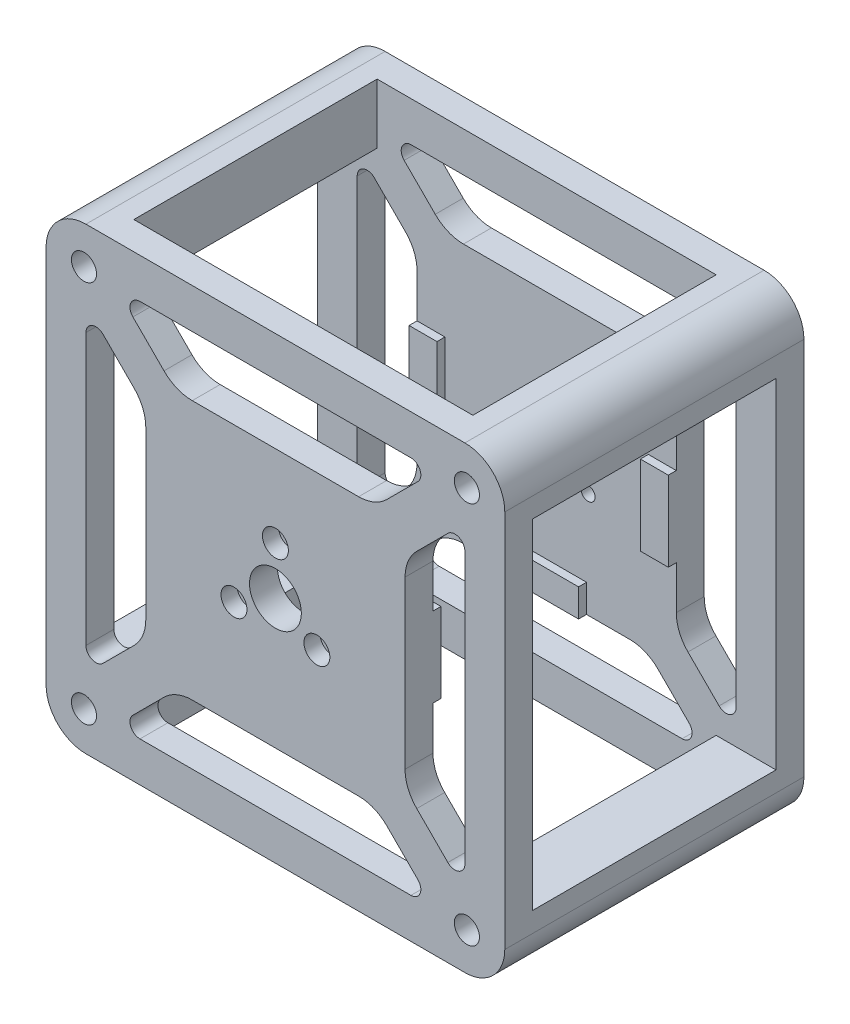
SolidWorks part; units mm, degrees
ref_plane "Front Plane" through (0, 0, 0) normal (0, 0, 1) x (1, 0, 0)
ref_plane "Top Plane" through (0, 0, 0) normal (0, 1, 0) x (1, 0, 0)
ref_plane "Right Plane" through (0, 0, 0) normal (1, 0, 0) x (0, 0, -1)
sketch "Sketch1" plane through (0, 0, 0) normal (0, 0, 1) x (1, 0, 0)
  line L1 (57.5, -57.5) -> (-57.5, -57.5)
  line L2 (57.5, -57.5) -> (57.5, 57.5)
  line L3 (57.5, 57.5) -> (-57.5, 57.5)
  line L4 (-57.5, -57.5) -> (-57.5, 57.5)
  line L5 (57.5, -57.5) -> (-57.5, 57.5) construction
  line L6 (57.5, 57.5) -> (-57.5, -57.5) construction
  point P0 (0, 0)
  dimension "D1" = 115
  dimension "D2" = 115
extrude "Boss-Extrude1" add sketch "Sketch1" along normal mid plane 75
ref_plane "Plane1" through (0, 0, 37.5) normal (0, 0, 1) x (1, 0, 0)
sketch "Sketch2" plane through (0, 0, 37.5) normal (0, 0, 1) x (1, 0, 0)
  line L1 (25.15, -25.15) -> (-25.15, -25.15)
  line L2 (25.15, -25.15) -> (25.15, 25.15)
  line L3 (25.15, 25.15) -> (-25.15, 25.15)
  line L4 (-25.15, -25.15) -> (-25.15, 25.15)
  line L5 (25.15, -25.15) -> (-25.15, 25.15) construction
  line L6 (25.15, 25.15) -> (-25.15, -25.15) construction
  point P0 (0, 0)
  dimension "D1" = 50.3
  dimension "D2" = 50.3
extrude "Cut-Extrude1" [suppressed] cut sketch "Sketch2" against normal blind 80
sketch "Sketch3" plane through (0, 0, 37.5) normal (0, 0, 1) x (1, 0, 0)
  circle A0 centre (-48, 48) radius 3.15
  dimension "D1" = 6.3
  dimension "D2" = 48
  dimension "D3" = 48
extrude "Cut-Extrude2" cut sketch "Sketch3" against normal blind 80 contours A0
mirror "Mirror1" about plane through (0, 0, 0) normal (0, 1, 0) of "Cut-Extrude2" second plane through (0, 0, 0) second plane normal (1, 0, 0)
fillet "Fillet1" radius 10 4 edges at (-57.5, -57.5, 0) (57.5, -57.5, 0) (-57.5, 57.5, 0) (57.5, 57.5, 0)
sketch "Sketch5" plane through (0, 0, 37.5) normal (0, 0, 1) x (1, 0, 0)
  line L0 (0, 61.1548) -> (0, -69.4595) construction
  line L1 (-40, 47.5) -> (-25, 47.5)
  line L2 (-25, 32.5) -> (25, 32.5)
  line L3 (-25, 32.5) -> (-25, 47.5) construction
  line L4 (-25, 47.5) -> (25, 47.5)
  line L5 (25, 32.5) -> (25, 47.5) construction
  line L6 (-25, 32.5) -> (25, 47.5) construction
  line L7 (-25, 47.5) -> (25, 32.5) construction
  line L8 (25, 47.5) -> (40, 47.5)
  line L9 (-25, 32.5) -> (-40, 47.5)
  line L10 (25, 32.5) -> (40, 47.5)
  point P3 (0, 40)
  dimension "D1" = 40
  dimension "D2" = 15
  dimension "D3" = 50
  dimension "D4" = 15
  dimension "D5" = 15
extrude "Cut-Extrude3" cut sketch "Sketch5" against normal blind 80
mirror "Mirror2" about plane through (0, 0, 0) normal (0, 1, 0) of "Cut-Extrude3"
sketch "Sketch8" plane through (0, 0, 37.5) normal (0, 0, 1) x (1, 0, 0)
  line L0 (-82.9503, 0) -> (98.9994, 0) construction
  line L1 (47.5, 25) -> (47.5, 40)
  line L2 (47.5, -25) -> (32.5, -25) construction
  line L3 (47.5, -25) -> (47.5, 25)
  line L4 (47.5, 25) -> (32.5, 25) construction
  line L5 (32.5, -25) -> (32.5, 25)
  line L6 (47.5, -25) -> (32.5, 25) construction
  line L7 (47.5, 25) -> (32.5, -25) construction
  line L8 (47.5, -25) -> (47.5, -40)
  line L9 (32.5, 25) -> (47.5, 40)
  line L10 (32.5, -25) -> (47.5, -40)
  point P3 (40, 0)
  dimension "D1" = 40
  dimension "D2" = 50
  dimension "D3" = 15
  dimension "D4" = 15
  dimension "D5" = 15
extrude "Cut-Extrude6" cut sketch "Sketch8" against normal blind 80
mirror "Mirror3" about plane through (0, 0, 0) normal (1, 0, 0) of "Cut-Extrude6"
fillet "Fillet2" radius 2.5 8 edges at (-40, -47.5, 0) (40, -47.5, 0) (47.5, -40, 0) (47.5, 40, 0) (-47.5, -40, 0) (40, 47.5, 0) (-47.5, 40, 0) (-40, 47.5, 0)
fillet "Fillet3" radius 10 8 edges at (32.5, 25, 0) (32.5, -25, 0) (25, -32.5, 0) (-25, -32.5, 0) (-32.5, -25, 0) (-32.5, 25, 0) (25, 32.5, 0) (-25, 32.5, 0)
ref_plane "Plane2" through (0, 57.5, 0) normal (0, 1, 0) x (1, 0, 0)
sketch "Sketch9" plane through (0, 57.5, 0) normal (0, 1, 0) x (1, 0, 0)
  line L1 (42.5, -30.5) -> (-42.5, -30.5)
  line L2 (42.5, -30.5) -> (42.5, 30.5)
  line L3 (42.5, 30.5) -> (-42.5, 30.5)
  line L4 (-42.5, -30.5) -> (-42.5, 30.5)
  line L5 (42.5, -30.5) -> (-42.5, 30.5) construction
  line L6 (42.5, 30.5) -> (-42.5, -30.5) construction
  point P0 (0, 0)
  dimension "D1" = 85
  dimension "D2" = 61
extrude "Cut-Extrude7" cut sketch "Sketch9" against normal blind 130
ref_plane "Plane3" through (57.5, 0, 0) normal (1, 0, 0) x (0, 0, -1)
sketch "Sketch10" plane through (57.5, 0, 0) normal (1, 0, 0) x (0, 0, -1)
  line L1 (30.5, -42.5) -> (-30.5, -42.5)
  line L2 (30.5, -42.5) -> (30.5, 42.5)
  line L3 (30.5, 42.5) -> (-30.5, 42.5)
  line L4 (-30.5, -42.5) -> (-30.5, 42.5)
  line L5 (30.5, -42.5) -> (-30.5, 42.5) construction
  line L6 (30.5, 42.5) -> (-30.5, -42.5) construction
  point P0 (0, 0)
  dimension "D1" = 85
  dimension "D2" = 61
extrude "Cut-Extrude8" cut sketch "Sketch10" against normal blind 120
fillet "Fillet4" [suppressed] radius 2
sketch "Sketch11" plane through (0, 0, 37.5) normal (0, 0, 1) x (1, 0, 0)
  line L1 (31, -31) -> (-31, -31)
  line L2 (31, -31) -> (31, 31)
  line L3 (31, 31) -> (-31, 31)
  line L4 (-31, -31) -> (-31, 31)
  line L5 (31, -31) -> (-31, 31) construction
  line L6 (31, 31) -> (-31, -31) construction
  point P0 (0, 0)
  dimension "D1" = 62
  dimension "D2" = 62
sketch "Sketch12" plane through (0, 0, 37.5) normal (0, 0, 1) x (1, 0, 0)
  circle A0 centre (0, 0) radius 6.5
  dimension "D1" = 13
extrude "Cut-Extrude9" cut sketch "Sketch12" against normal blind 80
sketch "Sketch13" plane through (0, 0, 37.5) normal (0, 0, 1) x (1, 0, 0)
  line L0 (0, 0) -> (0, 30.5063) construction
  circle A0 centre (0, 12) radius 1.75
  dimension "D1" = 3.5
  dimension "D2" = 12
extrude "Cut-Extrude10" cut sketch "Sketch13" against normal blind 80
pattern_circular "CirPattern1" count 3 over 360 about axis through (0, 0, 0) along (0, 0, 1) of "Cut-Extrude10"
sketch "Sketch14" plane through (0, 0, 37.5) normal (0, 0, 1) x (1, 0, 0)
  circle A0 centre (0, 12) radius 3.25
  dimension "D1" = 6.5
extrude "Cut-Extrude11" cut sketch "Sketch14" against normal blind 4
pattern_circular "CirPattern2" count 3 over 360 about axis through (0, 0, 0) along (0, 0, 1) of "Cut-Extrude11"
mirror "Mirror4" about plane through (0, 0, 0) normal (0, 0, 1) of "CirPattern2", "Cut-Extrude11"
extrude "Boss-Extrude2" [suppressed] add sketch "Sketch11" along normal blind 5
fillet "Fillet5" [suppressed] radius 10
sketch "Sketch17" plane through (0, 0, 0) normal (0, 0, 1) x (1, 0, 0)
  circle A0 centre (-48, 48) radius 4
  dimension "D1" = 8
extrude "Cut-Extrude12" cut sketch "Sketch17" against normal mid plane 60
pattern_circular "CirPattern3" count 4 over 360 about axis through (0, 0, 0) along (0, 0, 1) of "Cut-Extrude12"
ref_plane "Plane4" through (0, 0, -30.5) normal (0, 0, 1) x (1, 0, 0)
sketch "Sketch18" plane through (0, 0, -30.5) normal (0, 0, 1) x (1, 0, 0)
  line L0 (-77.1022, 0) -> (73.8481, 0) construction
  line L1 (0, 67.7017) -> (0, -65.8939) construction
  line L3 (-32.5, -10) -> (-25.5, -10)
  line L4 (-32.5, -10) -> (-32.5, 10)
  line L5 (-32.5, 10) -> (-25.5, 10)
  line L6 (-25.5, -10) -> (-25.5, 10)
  line L7 (-32.5, -10) -> (-25.5, 10) construction
  line L8 (-32.5, 10) -> (-25.5, -10) construction
  line L9 (32.5, -10) -> (25.5, -10)
  line L10 (32.5, -10) -> (32.5, 10)
  line L11 (32.5, 10) -> (25.5, 10)
  line L12 (25.5, -10) -> (25.5, 10)
  line L13 (32.5, -10) -> (25.5, 10) construction
  line L14 (32.5, 10) -> (25.5, -10) construction
  line L15 (10, -32.5) -> (-10, -32.5)
  line L16 (10, -32.5) -> (10, -25.5)
  line L17 (10, -25.5) -> (-10, -25.5)
  line L18 (-10, -32.5) -> (-10, -25.5)
  line L19 (10, -32.5) -> (-10, -25.5) construction
  line L20 (10, -25.5) -> (-10, -32.5) construction
  point P5 (-29, 0)
  point P10 (29, 0)
  point P15 (0, -29)
  dimension "D1" = 25.5
  dimension "D2" = 7
  dimension "D3" = 20
  dimension "D4" = 7
  dimension "D5" = 20
  dimension "D6" = 25.5
  dimension "D7" = 7
  dimension "D8" = 20
  dimension "D9" = 25.5
extrude "Boss-Extrude3" add sketch "Sketch18" along normal blind 2
mirror "Mirror5" about plane through (0, 0, 0) normal (0, 0, 1) of "Boss-Extrude3"
